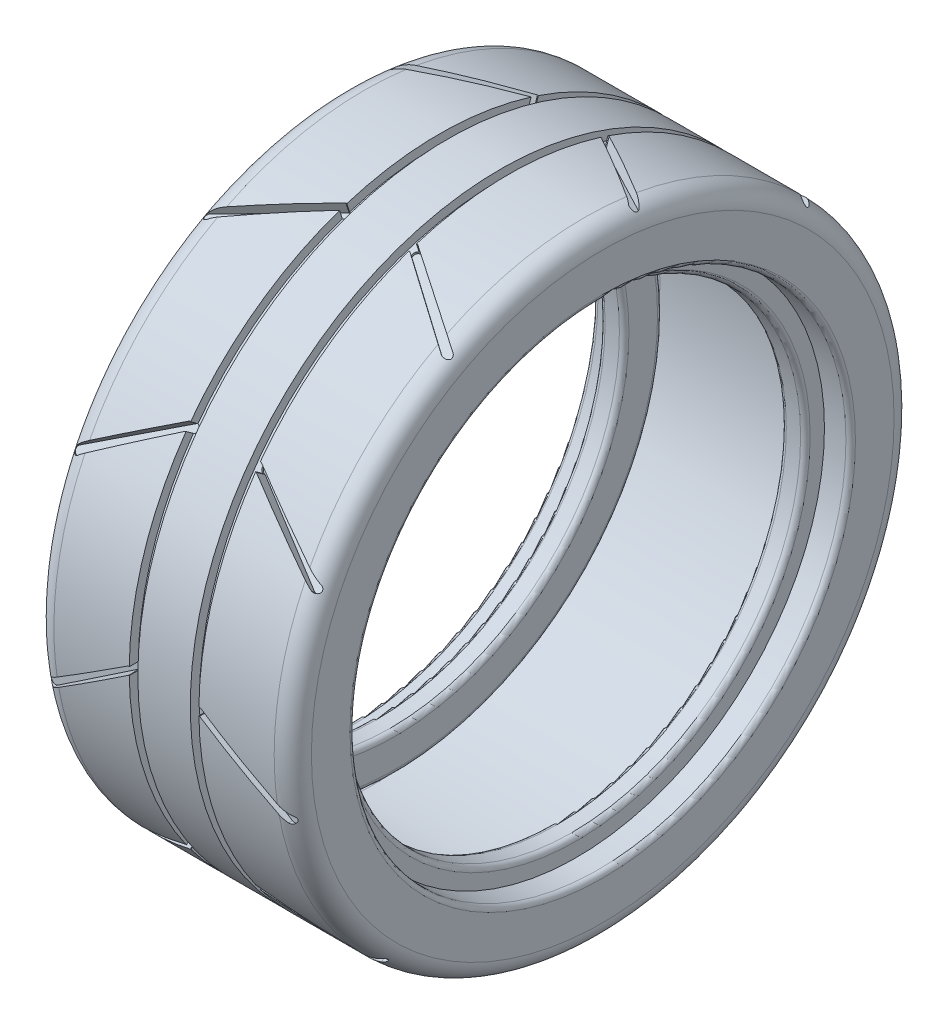
SolidWorks part; units mm, degrees
ref_plane "前视基准面" through (0, 0, 0) normal (0, 0, 1) x (1, 0, 0)
ref_plane "上视基准面" through (0, 0, 0) normal (0, 1, 0) x (1, 0, 0)
ref_plane "右视基准面" through (0, 0, 0) normal (1, 0, 0) x (0, 0, -1)
other "Configuration Table"
sketch "Tire Cross Section" plane through (0, 0, 0) normal (0, 1, 0) x (1, 0, 0)
  line L0 (0, 0) -> (0, 32.5) construction
  line L1 (13.5, 32.5) -> (-13.5, 32.5)
  line L2 (-13.5, 32.5) -> (-13.5, 26.5)
  line L3 (-13, 26) -> (-10.75, 26)
  line L4 (-10.75, 26) -> (-10.75, 24.5)
  line L5 (-10.25, 24) -> (-8.75, 24)
  line L6 (10.75, 26) -> (10.75, 24.5)
  line L7 (13, 26) -> (10.75, 26)
  line L8 (13.5, 32.5) -> (13.5, 26.5)
  line L9 (-8.25, 24.5) -> (-8.25, 27.5)
  line L10 (-8.75, 28) -> (-11, 28)
  line L11 (-11.5, 28.5) -> (-11.5, 30)
  line L12 (-11, 30.5) -> (11, 30.5)
  line L13 (11.5, 28.5) -> (11.5, 30)
  line L14 (8.25, 24.5) -> (8.25, 27.5)
  line L15 (8.75, 28) -> (11, 28)
  line L16 (8.75, 24) -> (10.25, 24)
  line L17 (0, 0) -> (-29.1572, 0) construction
  arc A0 (13, 26) -> (13.5, 26.5) centre (13, 26.5) ccw
  arc A1 (10.75, 24.5) -> (10.25, 24) centre (10.25, 24.5) cw
  arc A2 (8.25, 24.5) -> (8.75, 24) centre (8.75, 24.5) ccw
  arc A3 (8.25, 27.5) -> (8.75, 28) centre (8.75, 27.5) cw
  arc A4 (11.5, 28.5) -> (11, 28) centre (11, 28.5) cw
  arc A5 (11.5, 30) -> (11, 30.5) centre (11, 30) ccw
  arc A6 (-11.5, 30) -> (-11, 30.5) centre (-11, 30) cw
  arc A7 (-11, 28) -> (-11.5, 28.5) centre (-11, 28.5) cw
  arc A8 (-8.25, 27.5) -> (-8.75, 28) centre (-8.75, 27.5) ccw
  arc A9 (-8.25, 24.5) -> (-8.75, 24) centre (-8.75, 24.5) cw
  arc A10 (-10.75, 24.5) -> (-10.25, 24) centre (-10.25, 24.5) ccw
  arc A11 (-13.5, 26.5) -> (-13, 26) centre (-13, 26.5) ccw
  point P9 (0, 24)
  point P21 (0, 30.5)
  point P24 (13.5, 26)
  point P27 (10.75, 24)
  point P30 (8.25, 24)
  point P33 (8.25, 28)
  point P36 (11.5, 28)
  point P39 (11.5, 30.5)
  point P42 (-11.5, 30.5)
  point P45 (-11.5, 28)
  point P48 (-8.25, 28)
  point P51 (-8.25, 24)
  point P54 (-10.75, 24)
  point P57 (-13.5, 26)
  dimension "D10" = 0.5
  dimension "TireWidth" = 27
  dimension "D2" = 24
  dimension "CrownRadius" = 32.5
  dimension "D4" = 26
  dimension "D5" = 21.5
  dimension "D6" = 2
  dimension "D7" = 2.5
  dimension "D8" = 2
  dimension "D9" = 2
revolve "Tire Profile" add sketch "Tire Cross Section" angle 360 about L17
sketch "草图4" plane through (0, 0, 0) normal (0, 0, 1) x (1, 0, 0)
  line L0 (0, 0) -> (-20.571, 0) construction
  line L1 (-3.75, -0.6) -> (1.4, -0.6)
  line L2 (1.4, -0.6) -> (2.5, -3.5)
  line L3 (2.5, -3.5) -> (-6, -3.5)
  line L4 (-6, -3.5) -> (-7.5, 1.5)
  line L5 (-7.5, 1.5) -> (-5.13, 4)
  line L6 (-5.13, 4) -> (-3.75, -0.6)
  line L7 (-8.916, 1) -> (-7.416, -4)
  line L8 (-7.416, -4) -> (-8.9, -6)
  line L9 (-8.9, -6) -> (-13.4, -6)
  line L11 (-13.4, -6) -> (-13.4, -3)
  line L12 (-13.4, -3) -> (-10.8481, -3)
  line L13 (-10.8481, -3) -> (-11.1481, -2)
  line L14 (-11.1481, -2) -> (-13.4, -2)
  line L15 (-13.4, -2) -> (-13.4, 1)
  line L16 (-13.4, 1) -> (-8.916, 1)
  line L17 (-9.6601, 0) -> (-8.518, -3.8069)
  line L18 (-8.518, -3.8069) -> (-9.4032, -5)
  line L19 (-9.4032, -5) -> (-12.4, -5)
  line L20 (-12.4, -5) -> (-12.4, -4)
  line L21 (-12.4, -4) -> (-9.5041, -4)
  line L22 (-9.5041, -4) -> (-10.4041, -1)
  line L23 (-10.4041, -1) -> (-12.4, -1)
  line L24 (-12.4, -1) -> (-12.4, 0)
  line L25 (-12.4, 0) -> (-9.6601, 0)
  line L26 (-4.494, -1.6) -> (0.7098, -1.6)
  line L27 (0.7098, -1.6) -> (1.0512, -2.5)
  line L28 (1.0512, -2.5) -> (-5.256, -2.5)
  line L29 (-5.256, -2.5) -> (-6.3757, 1.2324)
  line L30 (-6.3757, 1.2324) -> (-5.5918, 2.0593)
  line L31 (-5.5918, 2.0593) -> (-4.494, -1.6)
  line L32 (13.4, -1) -> (8.916, -1)
  line L33 (8.916, -1) -> (7.416, 4)
  line L34 (7.416, 4) -> (8.9, 6)
  line L35 (8.9, 6) -> (13.4, 6)
  line L36 (13.4, 6) -> (13.4, 3)
  line L37 (13.4, 3) -> (10.8481, 3)
  line L38 (10.8481, 3) -> (11.1481, 2)
  line L39 (11.1481, 2) -> (13.4, 2)
  line L40 (13.4, 2) -> (13.4, -1)
  line L41 (9.6601, 0) -> (8.518, 3.8069)
  line L42 (8.518, 3.8069) -> (9.4032, 5)
  line L43 (9.4032, 5) -> (12.4, 5)
  line L44 (12.4, 5) -> (12.4, 4)
  line L45 (12.4, 4) -> (9.5041, 4)
  line L46 (9.5041, 4) -> (10.4041, 1)
  line L47 (10.4041, 1) -> (12.4, 1)
  line L48 (12.4, 1) -> (12.4, 0)
  line L49 (12.4, 0) -> (9.6601, 0)
  line L50 (5.13, -4) -> (3.75, 0.6)
  line L51 (3.75, 0.6) -> (-1.4, 0.6)
  line L52 (-1.4, 0.6) -> (-2.5, 3.5)
  line L53 (-2.5, 3.5) -> (6, 3.5)
  line L54 (6, 3.5) -> (7.5, -1.5)
  line L55 (7.5, -1.5) -> (5.13, -4)
  line L56 (4.494, 1.6) -> (-0.7098, 1.6)
  line L57 (-0.7098, 1.6) -> (-1.0512, 2.5)
  line L58 (-1.0512, 2.5) -> (5.256, 2.5)
  line L59 (5.256, 2.5) -> (6.3757, -1.2324)
  line L60 (6.3757, -1.2324) -> (5.5918, -2.0593)
  line L61 (5.5918, -2.0593) -> (4.494, 1.6)
  line L62 (-13.5, 32.5) -> (-13.5, -32.5) construction
  point P68 (0, 0)
  dimension "D4" = 1.2
  dimension "D5" = 7
  dimension "D6" = 5
  dimension "D7" = 2.8
  dimension "D8" = 12
  dimension "D9" = 7.5
  dimension "D10" = 15
  dimension "D11" = 3
  dimension "D12" = 8
  dimension "D13" = 1.5
  dimension "D14" = 3
  dimension "D15" = 7
  dimension "D16" = 1
  dimension "D17" = 5
  dimension "D18" = 4.5
  dimension "D19" = 1
  dimension "D20" = 0.1
  dimension "D1" = 1
  dimension "D2" = 1
  dimension "D3" = 2
sketch "草图5" plane through (0, 0, 0) normal (0, 0, 1) x (1, 0, 0)
  line L6 (1.4, -0.6) -> (-3.75, -0.6)
  line L7 (2.5, -3.5) -> (1.4, -0.6)
  line L8 (-6, -3.5) -> (2.5, -3.5)
  line L9 (-7.5, 1.5) -> (-6, -3.5)
  line L10 (-5.13, 4) -> (-7.5, 1.5)
  line L11 (-3.75, -0.6) -> (-5.13, 4)
  line L12 (1.1239, -0.6) -> (-3.4524, -0.6)
  line L13 (2.2945, -2.9581) -> (1.4979, -0.8581)
  line L14 (-5.7024, -3.5) -> (1.9205, -3.5)
  line L15 (-7.4334, 1.278) -> (-6.0855, -3.2149)
  line L16 (-5.605, 3.4989) -> (-7.3406, 1.6682)
  line L17 (-3.8355, -0.3149) -> (-4.9316, 3.3387)
  line L18 (3.75, 0.6) -> (5.13, -4)
  line L19 (-1.4, 0.6) -> (3.75, 0.6)
  line L20 (-2.5, 3.5) -> (-1.4, 0.6)
  line L21 (-9.4032, -5) -> (-8.518, -3.8069)
  line L22 (-12.4, -5) -> (-9.4032, -5)
  line L23 (-12.4, -4) -> (-12.4, -5)
  line L24 (-9.5041, -4) -> (-12.4, -4)
  line L25 (-10.4041, -1) -> (-9.5041, -4)
  line L26 (-12.4, -1) -> (-10.4041, -1)
  line L27 (-12.4, 0) -> (-12.4, -1)
  line L28 (-9.6601, 0) -> (-12.4, 0)
  line L29 (-8.518, -3.8069) -> (-9.6601, 0)
  line L30 (-9.2833, -4.8383) -> (-8.6375, -3.9681)
  line L31 (-12, -5) -> (-9.6045, -5)
  line L32 (-12.4, -4.4) -> (-12.4, -4.6)
  line L33 (-10.0417, -4) -> (-12, -4)
  line L34 (-10.3186, -1.2851) -> (-9.6586, -3.4851)
  line L35 (-12, -1) -> (-10.7017, -1)
  line L36 (-12.4, -0.4) -> (-12.4, -0.6)
  line L37 (-9.9577, 0) -> (-12, 0)
  line L38 (-8.5756, -3.6148) -> (-9.5746, -0.2851)
  line L39 (-10.8481, -3) -> (-13.4, -3)
  line L40 (-11.1481, -2) -> (-10.8481, -3)
  line L41 (-13.4, -2) -> (-11.1481, -2)
  line L42 (-13.4, 1) -> (-13.4, -2)
  line L43 (-8.916, 1) -> (-13.4, 1)
  line L44 (-7.416, -4) -> (-8.916, 1)
  line L45 (-8.9, -6) -> (-7.416, -4)
  line L46 (-13.4, -6) -> (-8.9, -6)
  line L47 (-13.4, -3) -> (-13.4, -6)
  line L48 (-11.3858, -3) -> (-13, -3)
  line L49 (-11.0626, -2.2851) -> (-11.0026, -2.4851)
  line L50 (-13, -2) -> (-11.4458, -2)
  line L51 (-13.4, 0.6) -> (-13.4, -1.6)
  line L52 (-9.2137, 1) -> (-13, 1)
  line L53 (-7.4737, -3.8078) -> (-8.8305, 0.7149)
  line L54 (-8.7801, -5.8383) -> (-7.5356, -4.1611)
  line L55 (-13, -6) -> (-9.1013, -6)
  line L56 (-13.4, -3.4) -> (-13.4, -5.6)
  line L57 (6, 3.5) -> (-2.5, 3.5)
  line L58 (7.5, -1.5) -> (6, 3.5)
  line L59 (5.13, -4) -> (7.5, -1.5)
  line L60 (3.8355, 0.3149) -> (4.9316, -3.3387)
  line L61 (-1.1239, 0.6) -> (3.4524, 0.6)
  line L62 (-2.2945, 2.9581) -> (-1.4979, 0.8581)
  line L63 (5.7024, 3.5) -> (-1.9205, 3.5)
  line L64 (7.4334, -1.278) -> (6.0855, 3.2149)
  line L65 (5.605, -3.4989) -> (7.3406, -1.6682)
  line L66 (-6.3757, 1.2324) -> (-5.256, -2.5)
  line L67 (-5.5918, 2.0593) -> (-6.3757, 1.2324)
  line L68 (-4.494, -1.6) -> (-5.5918, 2.0593)
  line L69 (0.7098, -1.6) -> (-4.494, -1.6)
  line L70 (1.0512, -2.5) -> (0.7098, -1.6)
  line L71 (-5.256, -2.5) -> (1.0512, -2.5)
  line L72 (-6.3091, 1.0105) -> (-5.3415, -2.2149)
  line L73 (-6.0668, 1.5582) -> (-6.2163, 1.4006)
  line L74 (-4.5795, -1.3149) -> (-5.3934, 1.398)
  line L75 (0.4337, -1.6) -> (-4.1964, -1.6)
  line L76 (0.8456, -1.9581) -> (0.8077, -1.8581)
  line L77 (-4.9584, -2.5) -> (0.4716, -2.5)
  line L78 (5.256, 2.5) -> (-1.0512, 2.5)
  line L79 (6.3757, -1.2324) -> (5.256, 2.5)
  line L80 (5.5918, -2.0593) -> (6.3757, -1.2324)
  line L81 (9.4032, 5) -> (8.518, 3.8069)
  line L82 (12.4, 5) -> (9.4032, 5)
  line L83 (12.4, 4) -> (12.4, 5)
  line L84 (9.5041, 4) -> (12.4, 4)
  line L85 (10.4041, 1) -> (9.5041, 4)
  line L86 (12.4, 1) -> (10.4041, 1)
  line L87 (12.4, 0) -> (12.4, 1)
  line L88 (9.6601, 0) -> (12.4, 0)
  line L89 (8.518, 3.8069) -> (9.6601, 0)
  line L90 (9.2833, 4.8383) -> (8.6375, 3.9681)
  line L91 (12, 5) -> (9.6045, 5)
  line L92 (12.4, 4.4) -> (12.4, 4.6)
  line L93 (10.0417, 4) -> (12, 4)
  line L94 (10.3186, 1.2851) -> (9.6586, 3.4851)
  line L95 (12, 1) -> (10.7017, 1)
  line L96 (12.4, 0.4) -> (12.4, 0.6)
  line L97 (9.9577, 0) -> (12, 0)
  line L98 (8.5756, 3.6148) -> (9.5746, 0.2851)
  line L99 (8.916, -1) -> (13.4, -1)
  line L100 (7.416, 4) -> (8.916, -1)
  line L101 (8.9, 6) -> (7.416, 4)
  line L102 (13.4, 6) -> (8.9, 6)
  line L103 (13.4, 3) -> (13.4, 6)
  line L104 (10.8481, 3) -> (13.4, 3)
  line L105 (11.1481, 2) -> (10.8481, 3)
  line L106 (13.4, 2) -> (11.1481, 2)
  line L107 (13.4, -1) -> (13.4, 2)
  line L108 (9.2137, -1) -> (13, -1)
  line L109 (7.4737, 3.8078) -> (8.8305, -0.7149)
  line L110 (8.7801, 5.8383) -> (7.5356, 4.1611)
  line L111 (13, 6) -> (9.1013, 6)
  line L112 (13.4, 3.4) -> (13.4, 5.6)
  line L113 (11.3858, 3) -> (13, 3)
  line L114 (11.0626, 2.2851) -> (11.0026, 2.4851)
  line L115 (13, 2) -> (11.4458, 2)
  line L116 (13.4, -0.6) -> (13.4, 1.6)
  line L117 (4.494, 1.6) -> (5.5918, -2.0593)
  line L118 (-0.7098, 1.6) -> (4.494, 1.6)
  line L119 (-1.0512, 2.5) -> (-0.7098, 1.6)
  line L120 (4.9584, 2.5) -> (-0.4716, 2.5)
  line L121 (6.3091, -1.0105) -> (5.3415, 2.2149)
  line L122 (6.0668, -1.5582) -> (6.2163, -1.4006)
  line L123 (4.5795, 1.3149) -> (5.3934, -1.398)
  line L124 (-0.4337, 1.6) -> (4.1964, 1.6)
  line L125 (-0.8456, 1.9581) -> (-0.8077, 1.8581)
  arc A0 (-0.4337, 1.6) -> (-0.8077, 1.8581) centre (-0.4337, 2) cw
  arc A1 (4.5795, 1.3149) -> (4.1964, 1.6) centre (4.1964, 1.2) ccw
  arc A2 (13, 2) -> (13.4, 1.6) centre (13, 1.6) cw
  arc A3 (11.0626, 2.2851) -> (11.4458, 2) centre (11.4458, 2.4) ccw
  arc A4 (6.0668, -1.5582) -> (5.3934, -1.398) centre (5.7766, -1.2831) cw
  arc A5 (11.3858, 3) -> (11.0026, 2.4851) centre (11.3858, 2.6) ccw
  arc A6 (13.4, 3.4) -> (13, 3) centre (13, 3.4) cw
  arc A7 (6.3091, -1.0105) -> (6.2163, -1.4006) centre (5.926, -1.1254) cw
  arc A8 (13, 6) -> (13.4, 5.6) centre (13, 5.6) cw
  arc A9 (9.9577, 0) -> (9.5746, 0.2851) centre (9.9577, 0.4) cw
  arc A10 (12.4, 0.4) -> (12, 0) centre (12, 0.4) cw
  arc A11 (8.7801, 5.8383) -> (9.1013, 6) centre (9.1013, 5.6) cw
  arc A12 (12, 1) -> (12.4, 0.6) centre (12, 0.6) cw
  arc A13 (4.9584, 2.5) -> (5.3415, 2.2149) centre (4.9584, 2.1) cw
  arc A14 (10.3186, 1.2851) -> (10.7017, 1) centre (10.7017, 1.4) ccw
  arc A15 (7.4737, 3.8078) -> (7.5356, 4.1611) centre (7.8568, 3.9228) cw
  arc A16 (10.0417, 4) -> (9.6586, 3.4851) centre (10.0417, 3.6) ccw
  arc A17 (-0.4716, 2.5) -> (-0.8456, 1.9581) centre (-0.4716, 2.1) ccw
  arc A18 (12.4, 4.4) -> (12, 4) centre (12, 4.4) cw
  arc A19 (9.2137, -1) -> (8.8305, -0.7149) centre (9.2137, -0.6) cw
  arc A20 (0.8456, -1.9581) -> (0.4716, -2.5) centre (0.4716, -2.1) cw
  arc A21 (12, 5) -> (12.4, 4.6) centre (12, 4.6) cw
  arc A22 (0.4337, -1.6) -> (0.8077, -1.8581) centre (0.4337, -2) cw
  arc A23 (13, -1) -> (13.4, -0.6) centre (13, -0.6) ccw
  arc A24 (-4.5795, -1.3149) -> (-4.1964, -1.6) centre (-4.1964, -1.2) ccw
  arc A25 (9.2833, 4.8383) -> (9.6045, 5) centre (9.6045, 4.6) cw
  arc A26 (7.4334, -1.278) -> (7.3406, -1.6682) centre (7.0503, -1.393) cw
  arc A27 (-6.0668, 1.5582) -> (-5.3934, 1.398) centre (-5.7766, 1.2831) cw
  arc A28 (5.7024, 3.5) -> (6.0855, 3.2149) centre (5.7024, 3.1) cw
  arc A29 (-13, -6) -> (-13.4, -5.6) centre (-13, -5.6) cw
  arc A30 (8.6375, 3.9681) -> (8.5756, 3.6148) centre (8.9588, 3.7297) ccw
  arc A31 (-8.7801, -5.8383) -> (-9.1013, -6) centre (-9.1013, -5.6) cw
  arc A32 (-2.2945, 2.9581) -> (-1.9205, 3.5) centre (-1.9205, 3.1) cw
  arc A33 (-7.4737, -3.8078) -> (-7.5356, -4.1611) centre (-7.8568, -3.9228) cw
  arc A34 (-6.3091, 1.0105) -> (-6.2163, 1.4006) centre (-5.926, 1.1254) cw
  arc A35 (-9.2137, 1) -> (-8.8305, 0.7149) centre (-9.2137, 0.6) cw
  arc A36 (-1.1239, 0.6) -> (-1.4979, 0.8581) centre (-1.1239, 1) cw
  arc A37 (-13.4, 0.6) -> (-13, 1) centre (-13, 0.6) cw
  arc A38 (-9.9577, 0) -> (-9.5746, -0.2851) centre (-9.9577, -0.4) cw
  arc A39 (-5.3415, -2.2149) -> (-4.9584, -2.5) centre (-4.9584, -2.1) ccw
  arc A40 (-12.4, -0.4) -> (-12, 0) centre (-12, -0.4) cw
  arc A41 (-13, -2) -> (-13.4, -1.6) centre (-13, -1.6) cw
  arc A42 (-12, -1) -> (-12.4, -0.6) centre (-12, -0.6) cw
  arc A43 (3.8355, 0.3149) -> (3.4524, 0.6) centre (3.4524, 0.2) ccw
  arc A44 (-10.3186, -1.2851) -> (-10.7017, -1) centre (-10.7017, -1.4) ccw
  arc A45 (-11.0626, -2.2851) -> (-11.4458, -2) centre (-11.4458, -2.4) ccw
  arc A46 (-10.0417, -4) -> (-9.6586, -3.4851) centre (-10.0417, -3.6) ccw
  arc A47 (4.9316, -3.3387) -> (5.605, -3.4989) centre (5.3147, -3.2237) ccw
  arc A48 (-12.4, -4.4) -> (-12, -4) centre (-12, -4.4) cw
  arc A49 (-11.3858, -3) -> (-11.0026, -2.4851) centre (-11.3858, -2.6) ccw
  arc A50 (-5.605, 3.4989) -> (-4.9316, 3.3387) centre (-5.3147, 3.2237) cw
  arc A51 (-12, -5) -> (-12.4, -4.6) centre (-12, -4.6) cw
  arc A52 (-7.4334, 1.278) -> (-7.3406, 1.6682) centre (-7.0503, 1.393) cw
  arc A53 (-13, -3) -> (-13.4, -3.4) centre (-13, -3.4) ccw
  arc A54 (-5.7024, -3.5) -> (-6.0855, -3.2149) centre (-5.7024, -3.1) cw
  arc A55 (-9.2833, -4.8383) -> (-9.6045, -5) centre (-9.6045, -4.6) cw
  arc A56 (2.2945, -2.9581) -> (1.9205, -3.5) centre (1.9205, -3.1) cw
  arc A57 (-8.6375, -3.9681) -> (-8.5756, -3.6148) centre (-8.9588, -3.7297) ccw
  arc A58 (1.1239, -0.6) -> (1.4979, -0.8581) centre (1.1239, -1) cw
  arc A59 (-3.4524, -0.6) -> (-3.8355, -0.3149) centre (-3.4524, -0.2) cw
  dimension "D9" = 0.4
  dimension "D1" = 0
  dimension "D2" = 0
  dimension "D3" = 0
  dimension "D4" = 0
  dimension "D5" = 0
  dimension "D6" = 0
  dimension "D7" = 0
  dimension "D8" = 0
wrap "Legacy - Raised Tread Wrap" [suppressed] sketch "草图5" source sketch "草图5" thickness 2 parameters "D1"=2
pattern_circular "Legacy - Raised Tread Pattern" [suppressed] count 24 over 360
sketch "草图6" [suppressed] plane through (0, 0, 0) normal (0, 1, 0) x (1, 0, 0)
  line L0 (-13.5, 32) -> (-13.5, 34) construction
  line L1 (-13.5, 34) -> (-11.5, 34)
  line L2 (-26.422, 0) -> (0, 0) construction
  line L3 (0, 0) -> (0, 47.4685) construction
  line L7 (-13.5, 32) -> (-13.5, 23.6491)
  line L8 (-13.5, 24.4882) -> (-13.5, 22.81) construction
  line L9 (-13.5, 23.6491) -> (-14.5, 23.6491)
  line L10 (-14.5, 23.6491) -> (-14.5, 34)
  line L11 (-14.5, 34) -> (-13.5, 34)
  line L12 (-13.5, 33.0007) -> (-13.5, 32.3606) construction
  line L13 (13.5, 32) -> (13.5, 34) construction
  line L14 (14.5, 34) -> (13.5, 34)
  line L15 (14.5, 23.6491) -> (14.5, 34)
  line L16 (13.5, 23.6491) -> (14.5, 23.6491)
  line L17 (13.5, 32) -> (13.5, 23.6491)
  line L18 (13.5, 34) -> (11.5, 34)
  arc A0 (-11.5, 34) -> (-13.5, 32) centre (-11.5, 32) ccw
  arc A2 (11.5, 34) -> (13.5, 32) centre (11.5, 32) cw
  dimension "D1" = 34
  dimension "D2" = 2
  dimension "D3" = 1
revolve "Legacy - Shoulder Trim" [suppressed] cut sketch "草图6" angle 360 about L2
ref_axis "Axle Axis" through (-14.85, 0, 0) along (1, 0, 0)
sketch "Shoulder Radius Sections" plane through (0, 0, 0) normal (0, 1, 0) x (1, 0, 0)
  line L0 (-13.5, 30.55) -> (-13.9, 30.55)
  line L1 (-13.9, 30.55) -> (-13.9, 33.5)
  line L2 (-13.9, 33.5) -> (-11.55, 33.5)
  line L3 (-11.55, 33.5) -> (-11.55, 32.5)
  line L4 (13.5, 30.55) -> (13.9, 30.55)
  line L5 (13.9, 30.55) -> (13.9, 33.5)
  line L6 (13.9, 33.5) -> (11.55, 33.5)
  line L7 (11.55, 33.5) -> (11.55, 32.5)
  arc A0 (-11.55, 32.5) -> (-13.5, 30.55) centre (-11.55, 30.55) ccw
  arc A1 (11.55, 32.5) -> (13.5, 30.55) centre (11.55, 30.55) cw
revolve "Rounded Shoulders" cut sketch "Shoulder Radius Sections" angle 360 about axis through (-14.85, 0, 0) along (1, 0, 0)
sketch "Center Groove Sections" plane through (0, 0, 0) normal (0, 1, 0) x (1, 0, 0)
  line L0 (-2.75, 31.55) -> (-3.65, 31.55)
  line L1 (-3.65, 31.55) -> (-3.65, 34)
  line L2 (-3.65, 34) -> (-2.75, 34)
  line L3 (-2.75, 34) -> (-2.75, 31.55)
  line L4 (2.75, 31.55) -> (3.65, 31.55)
  line L5 (3.65, 31.55) -> (3.65, 34)
  line L6 (3.65, 34) -> (2.75, 34)
  line L7 (2.75, 34) -> (2.75, 31.55)
revolve "Twin Center Grooves" cut sketch "Center Groove Sections" angle 360 about axis through (-14.85, 0, 0) along (1, 0, 0)
ref_plane "Shoulder Groove Depth Plane" through (0, 0, 31.35) normal (0, 0, 1) x (1, 0, 0)
sketch "Mirrored Shoulder Groove Profiles" plane through (0, 0, 31.35) normal (0, 0, 1) x (1, 0, 0)
  line L0 (-3.72, -0.44) -> (-12.32, -6.22)
  line L1 (-12.8, -5.5) -> (-3.76, 0.39)
  line L2 (3.72, -0.44) -> (12.32, -6.22)
  line L3 (12.8, -5.5) -> (3.76, 0.39)
  arc A0 (-12.32, -6.22) -> (-12.8, -5.5) centre (-12.5011, -5.8207) cw
  arc A1 (-3.76, 0.39) -> (-3.72, -0.44) centre (-3.7661, -0.0263) cw
  arc A2 (12.32, -6.22) -> (12.8, -5.5) centre (12.5011, -5.8207) ccw
  arc A3 (3.76, 0.39) -> (3.72, -0.44) centre (3.7661, -0.0263) ccw
extrude "Shoulder Groove Pair" cut sketch "Mirrored Shoulder Groove Profiles" along normal through all
pattern_circular "Circular Tread Pattern" count 10 over 360 about axis through (0, 0, 0) along (1, 0, 0) of "Shoulder Groove Pair"
equation "\"TireOD\"= 65mm"
equation "\"TireWidth\"= 27mm"
equation "\"CrownRadius@Tire Cross Section\" = \"TireOD\" / 2"
equation "\"TireWidth@Tire Cross Section\" = \"TireWidth\""
equation "\"GrooveDepth\"= 1.15mm"
equation "\"GroovePlaneOffset@Shoulder Groove Depth Plane\" = \"TireOD\" / 2 - \"GrooveDepth\""
